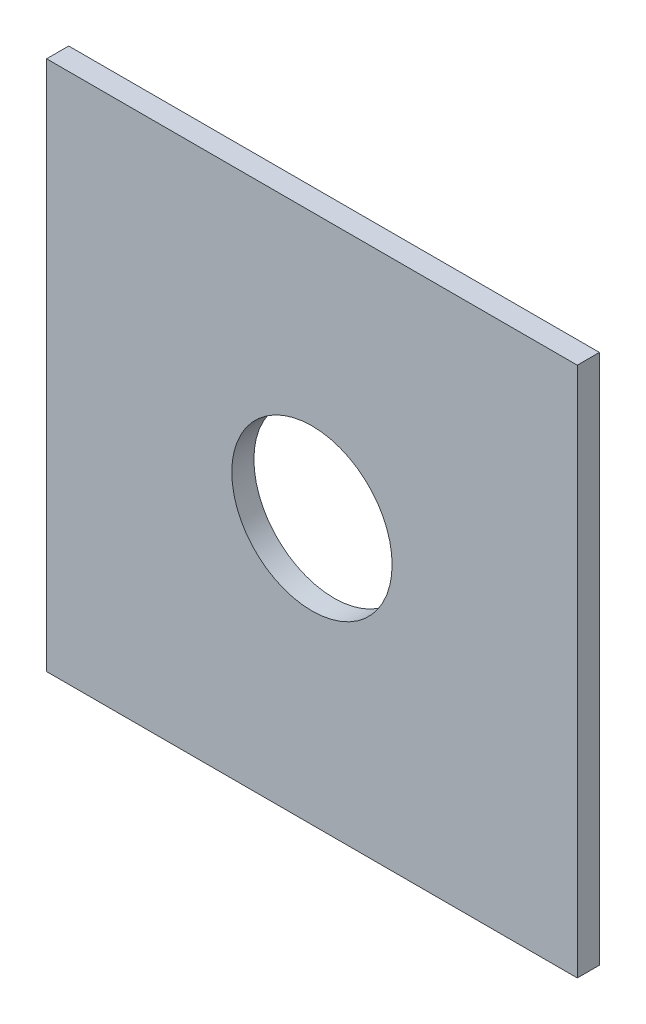
SolidWorks part; units mm, degrees
material "Mahogany"
ref_plane "Front Plane" through (0, 0, 0) normal (0, 0, 1) x (1, 0, 0)
ref_plane "Top Plane" through (0, 0, 0) normal (0, 1, 0) x (1, 0, 0)
ref_plane "Right Plane" through (0, 0, 0) normal (1, 0, 0) x (0, 0, -1)
sketch "Sketch1" plane through (0, 0, 0) normal (0, 0, 1) x (1, 0, 0)
  line L1 (152.4, 152.4) -> (-152.4, 152.4)
  line L2 (152.4, 152.4) -> (152.4, -152.4)
  line L3 (152.4, -152.4) -> (-152.4, -152.4)
  line L4 (-152.4, 152.4) -> (-152.4, -152.4)
  line L5 (152.4, 152.4) -> (-152.4, -152.4) construction
  line L6 (152.4, -152.4) -> (-152.4, 152.4) construction
  circle A0 centre (0, 0) radius 46.0375
  point P0 (0, 0)
  dimension "D3" = 92.075
  dimension "D1" = 304.8
  dimension "D2" = 304.8
extrude "Boss-Extrude1" add sketch "Sketch1" along normal blind 12.7
sketch "Sketch2" plane through (0, 0, 0) normal (0, 0, 1) x (1, 0, 0)
  line L0 (-71.842, 71.842) -> (0, 0) construction
  line L1 (0, 0) -> (71.842, -71.842) construction
  line L2 (0, 0) -> (152.4, 0) construction
  line L3 (152.4, -152.4) -> (152.4, 152.4) construction
  circle A0 centre (-71.842, 71.842) radius 7.9375
  circle A1 centre (71.842, -71.842) radius 7.9375
  dimension "D2" = 15.875
  dimension "D3" = 15.875
  dimension "D1" = 101.6
  dimension "D4" = 45
extrude "Cut-Extrude1" cut sketch "Sketch2" along normal offset from surface (9.525 mm away) 3.175 up to face at (0, 0, 12.7)
